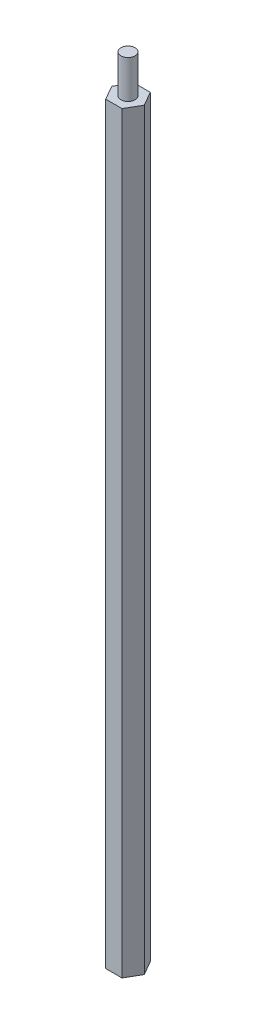
SolidWorks part; units mm, degrees
ref_plane "Front Plane" through (0, 0, 0) normal (0, 0, 1) x (1, 0, 0)
ref_plane "Top Plane" through (0, 0, 0) normal (0, 1, 0) x (1, 0, 0)
ref_plane "Right Plane" through (0, 0, 0) normal (1, 0, 0) x (0, 0, -1)
sketch "Sketch3" plane through (0, 0, 0) normal (0, 1, 0) x (1, 0, 0)
  line L1 (-3.4641, 0) -> (-1.7321, -3)
  line L2 (-1.7321, -3) -> (1.7321, -3)
  line L3 (1.7321, -3) -> (3.4641, 0)
  line L4 (3.4641, 0) -> (1.7321, 3)
  line L5 (1.7321, 3) -> (-1.7321, 3)
  line L6 (-1.7321, 3) -> (-3.4641, 0)
  circle A0 centre (0, 0) radius 3 construction
  dimension "D1" = 6
extrude "Boss-Extrude1" add sketch "Sketch3" along normal blind 160
sketch "Sketch5" plane through (0, 160, 0) normal (0, 1, 0) x (1, 0, 0)
  circle A0 centre (0, 0) radius 1.5
  dimension "D1" = 3
extrude "Boss-Extrude2" add sketch "Sketch5" along normal blind 8.0916
sketch "Sketch6" plane through (0, 0, 0) normal (0, -1, 0) x (1, 0, 0)
  circle A0 centre (0, 0) radius 1.5
extrude "Cut-Extrude1" cut sketch "Sketch6" against normal blind 4
